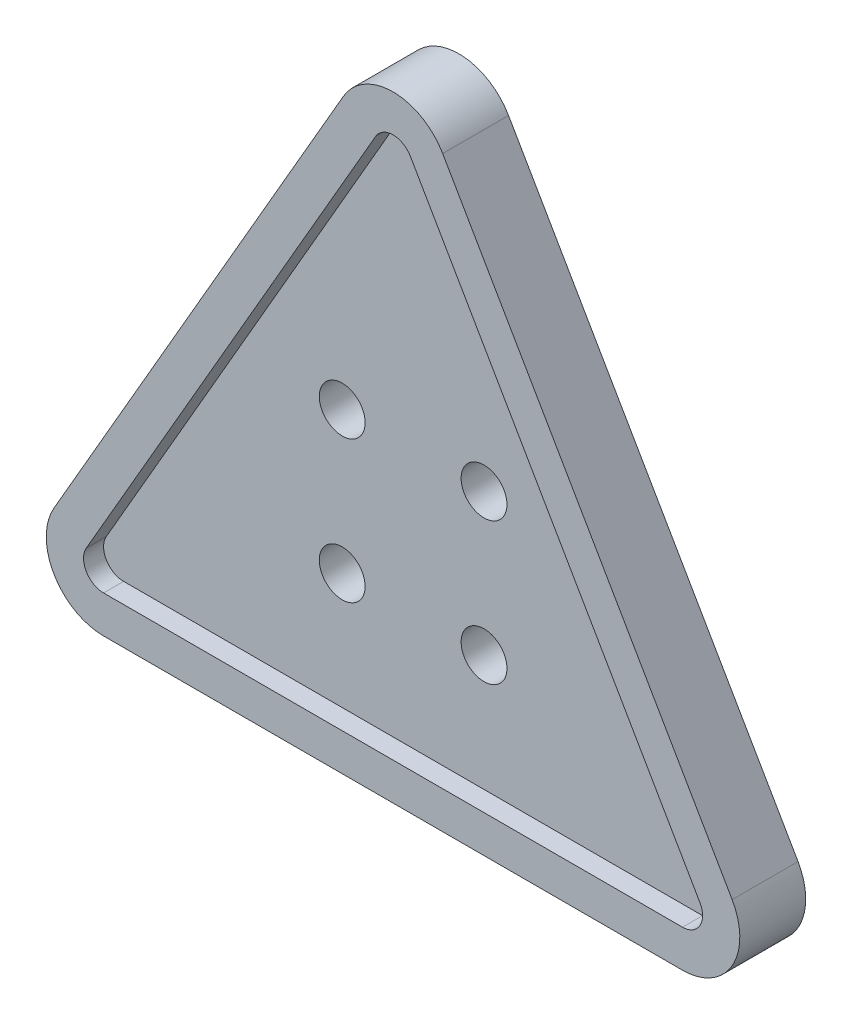
SolidWorks part; units mm, degrees
ref_plane "Front Plane" through (0, 0, 0) normal (0, 0, 1) x (1, 0, 0)
ref_plane "Top Plane" through (0, 0, 0) normal (0, 1, 0) x (1, 0, 0)
ref_plane "Right Plane" through (0, 0, 0) normal (1, 0, 0) x (0, 0, -1)
sketch "Sketch1" plane through (0, 0, 0) normal (0, 0, 1) x (1, 0, 0)
  line L0 (-3.4641, 25.3333) -> (-23.6714, -9.6667)
  line L1 (-4.9497, 4.9497) -> (4.9497, 4.9497) construction
  line L2 (-4.9497, 4.9497) -> (-4.9497, -4.9497) construction
  line L3 (-4.9497, -4.9497) -> (4.9497, -4.9497) construction
  line L4 (4.9497, 4.9497) -> (4.9497, -4.9497) construction
  line L5 (-4.9497, 4.9497) -> (4.9497, -4.9497) construction
  line L6 (-4.9497, -4.9497) -> (4.9497, 4.9497) construction
  line L12 (-20.2073, -15.6667) -> (20.2073, -15.6667)
  line L13 (23.6714, -9.6667) -> (3.4641, 25.3333)
  line L14 (27.1355, -15.6667) -> (-13.5677, 7.8333) construction
  line L15 (-13.5677, 7.8333) -> (-27.1355, -15.6667) construction
  line L16 (-27.1355, -15.6667) -> (13.5677, 7.8333) construction
  line L17 (13.5677, 7.8333) -> (0, 31.3333) construction
  line L18 (0, 31.3333) -> (0, -15.6667) construction
  circle A1 centre (-4.9497, 4.9497) radius 1.6
  circle A2 centre (4.9497, 4.9497) radius 1.6
  circle A3 centre (4.9497, -4.9497) radius 1.6
  circle A4 centre (-4.9497, -4.9497) radius 1.6
  arc A5 (-23.6714, -9.6667) -> (-20.2073, -15.6667) centre (-20.2073, -11.6667) ccw
  arc A6 (-3.4641, 25.3333) -> (3.4641, 25.3333) centre (0, 23.3333) cw
  arc A7 (20.2073, -15.6667) -> (23.6714, -9.6667) centre (20.2073, -11.6667) ccw
  point P2 (89.8385, 101.5052)
  point P11 (0, 0)
  point P16 (151.6069, -5.4809)
  point P17 (-53.8734, 13.8767)
  point P18 (0, 0)
  point P19 (45.7884, -26.4359)
  point P29 (0, 27.3333)
  dimension "D1" = 4
  dimension "D3" = 3.2
  dimension "D4" = 43
  dimension "D2" = 14
extrude "Boss-Extrude1" add sketch "Sketch1" along normal blind 4.6
sketch "Sketch4" plane through (0, 0, 4.6) normal (0, 0, 1) x (1, 0, 0)
  line L6 (-20.2073, -13.0667) -> (20.2073, -13.0667)
  line L7 (21.4197, -10.9667) -> (1.2124, 24.0333)
  line L8 (-1.2124, 24.0333) -> (-21.4197, -10.9667)
  line L9 (-20.2073, -13.0667) -> (20.2073, -13.0667)
  line L10 (21.4197, -10.9667) -> (1.2124, 24.0333)
  line L11 (-1.2124, 24.0333) -> (-21.4197, -10.9667)
  arc A6 (-21.4197, -10.9667) -> (-20.2073, -13.0667) centre (-20.2073, -11.6667) ccw
  arc A7 (20.2073, -13.0667) -> (21.4197, -10.9667) centre (20.2073, -11.6667) ccw
  arc A8 (1.2124, 24.0333) -> (-1.2124, 24.0333) centre (0, 23.3333) ccw
  arc A9 (-21.4197, -10.9667) -> (-20.2073, -13.0667) centre (-20.2073, -11.6667) ccw
  arc A10 (20.2073, -13.0667) -> (21.4197, -10.9667) centre (20.2073, -11.6667) ccw
  arc A11 (1.2124, 24.0333) -> (-1.2124, 24.0333) centre (0, 23.3333) ccw
  dimension "D1" = 2.6
extrude "Cut-Extrude3" cut sketch "Sketch4" against normal blind 1.4
